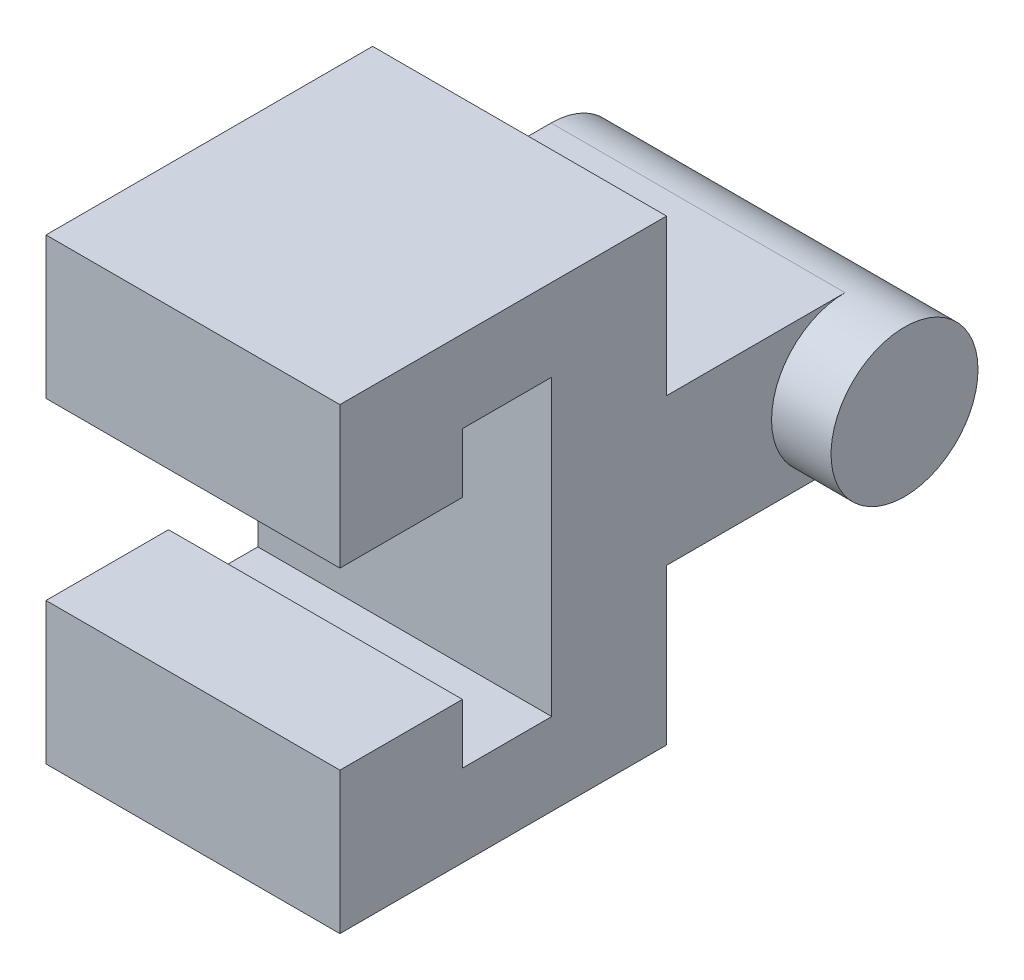
SolidWorks part; units mm, degrees
ref_plane "Front Plane" through (0, 0, 0) normal (1, 0, 0) x (0, 1, 0)
ref_plane "Top Plane" through (0, 0, 0) normal (0, 0, 1) x (0, 1, 0)
ref_plane "Right Plane" through (0, 0, 0) normal (0, 1, 0) x (-1, 0, 0)
sketch "Sketch2" plane through (0, 0, 0) normal (1, 0, 0) x (0, 1, 0)
  circle A0 centre (0, 0) radius 31.369
  dimension "D1" = 62.738
extrude "Boss-Extrude1" add sketch "Sketch2" along normal blind 25.4 contours A0
sketch "Sketch4" plane through (0, 0, 0) normal (-1, 0, 0) x (0, -1, 0)
  line L1 (31.369, 0) -> (31.369, 76.2)
  line L2 (31.369, 76.2) -> (-31.369, 76.2)
  line L3 (-31.369, 76.2) -> (-31.369, 0)
  circle A0 centre (0, 0) radius 31.369 construction
  arc A1 (-31.369, 0) -> (31.369, 0) centre (0, 0) ccw
  dimension "D1" = 76.2
  dimension "D2" = 62.738
extrude "Boss-Extrude2" add sketch "Sketch4" along normal blind 125.476
sketch "Sketch5" plane through (0, 0, 76.2) normal (0, 0, 1) x (1, 0, 0)
  line L0 (0, 0) -> (0, 62.7473)
  line L1 (0, -31.369) -> (0, 31.369) construction
  line L2 (0, 62.7473) -> (-125.476, 62.7473)
  line L3 (-125.476, 62.7473) -> (-125.476, -62.7473)
  line L4 (-125.476, -62.7473) -> (0, -62.7473)
  line L5 (0, -62.7473) -> (0, 0)
  line L6 (-125.476, -31.369) -> (-125.476, 31.369) construction
  dimension "D1" = 125.4945
extrude "Boss-Extrude3" add sketch "Sketch5" along normal blind 49.022
sketch "Sketch8" plane through (0, 62.7473, 0) normal (0, 1, 0) x (-1, 0, 0)
  line L1 (0, 125.222) -> (125.476, 125.222)
  line L2 (0, 125.222) -> (0, 76.2)
  line L3 (0, 76.2) -> (125.476, 76.2)
  line L4 (125.476, 125.222) -> (125.476, 76.2)
extrude "Boss-Extrude4" add sketch "Sketch8" along normal blind 35.052
sketch "Sketch9" plane through (0, -62.7473, 0) normal (0, -1, 0) x (1, 0, 0)
  line L1 (-125.476, 125.222) -> (0, 125.222)
  line L2 (-125.476, 125.222) -> (-125.476, 76.2)
  line L3 (-125.476, 76.2) -> (0, 76.2)
  line L4 (0, 125.222) -> (0, 76.2)
extrude "Boss-Extrude5" add sketch "Sketch9" along normal blind 35.052
sketch "Sketch10" plane through (0, 0, 125.222) normal (0, 0, 1) x (1, 0, 0)
  line L0 (0, -97.7993) -> (0, 97.7993) construction
  line L1 (-125.476, 97.7993) -> (0, 97.7993)
  line L2 (-125.476, 97.7993) -> (-125.476, 62.7473)
  line L3 (-125.476, 62.7473) -> (0, 62.7473)
  line L4 (0, 97.7993) -> (0, 62.7473)
  line L6 (-125.476, -97.7993) -> (0, -97.7993)
  line L7 (-125.476, -97.7993) -> (-125.476, -62.7473)
  line L8 (-125.476, -62.7473) -> (0, -62.7473)
  line L9 (0, -97.7993) -> (0, -62.7473)
  dimension "D1" = 35.052
  dimension "D2" = 35.052
extrude "Boss-Extrude6" add sketch "Sketch10" along normal blind 38.1
sketch "Sketch12" plane through (0, 0, 163.322) normal (0, 0, 1) x (1, 0, 0)
  line L0 (0, -62.7473) -> (0, 62.7473) construction
  line L1 (-125.476, 97.7993) -> (0, 97.7993)
  line L2 (-125.476, 97.7993) -> (-125.476, 37.3473)
  line L3 (-125.476, 37.3473) -> (0, 37.3473)
  line L4 (0, 97.7993) -> (0, 37.3473)
  line L5 (-125.476, 62.7473) -> (-125.476, -62.7473) construction
  line L6 (0, -97.7993) -> (-125.476, -97.7993)
  line L7 (0, -97.7993) -> (0, -37.3473)
  line L8 (0, -37.3473) -> (-125.476, -37.3473)
  line L9 (-125.476, -97.7993) -> (-125.476, -37.3473)
  dimension "D1" = 60.452
extrude "Boss-Extrude7" add sketch "Sketch12" along normal blind 52.324
equation "\"Sy\"= 36000'Yield Strength (Psi)"
equation "\"P\"= 800'Full Load (Lbf)"
equation "\"F\"= 400'Split Load (Lbf)"
equation "\"FS\"= 4'Factor Safety"
equation "\"StressA\"= \"Sy\" / \"FS\"'Allowed Stress (Psi)"
equation "\"E\"= 29000'Modulus of Elasticity (psi)"
equation "\"L\"= 1'Length Cylinder (in)"
equation "\"deltaM\"= 0.005'Max deflection (in)"
equation "\"d\" = ( ( 64 * \"P\" * \"L\" ) / ( 3 * \"E\" * pi * \"deltaM\" ) ) ^ ( 1 / 4 )'diameter cylinder (in)"
equation "\"L2\"= 3'Length of feature B (in)"
equation "\"w\"= ( ( 4 * \"P\" * ( \"L2\" * \"L2\" * \"L2\" ) ) / ( \"E\" * \"deltaM\" ) ) ^ ( 1 / 4 )'Width feature B (in)"
equation "\"B1\"= 3'Base of feature C (in)"
equation "\"Lbab\"= 2.5'Length of Rigid T Beam (in)"
equation "\"H1\"= ( ( \"P\" * ( \"Lbab\" ^ 3 ) ) / ( 4 * \"E\" * \"B1\" * \"deltaM\" ) ) ^ ( 1 / 3 )'Height of Feature C (in)"
equation "\"Hd\"= 1.5'Height of feature D (in)"
equation "\"td\"= ( \"F\" * \"Hd\" ) / ( \"B1\" * \"E\" * \"deltaM\" )'Thickness of Feature D (in)"
equation "\"Lc\"= 1.499'Heifght of Riged T Beam (in)"
equation "\"Lb\"= 1'A length of Rigid T Beam (in)"
equation "\"tf\"= \"Lb\" + \"td\"'Thickness of Feature F (in)"
equation "\"Hf\"= ( ( \"F\" * \"tf\" * 4 ) / ( \"E\" * \"B1\" * \"deltaM\" ) ) ^ ( 1 / 3 )'Height of Feature F (in)"
